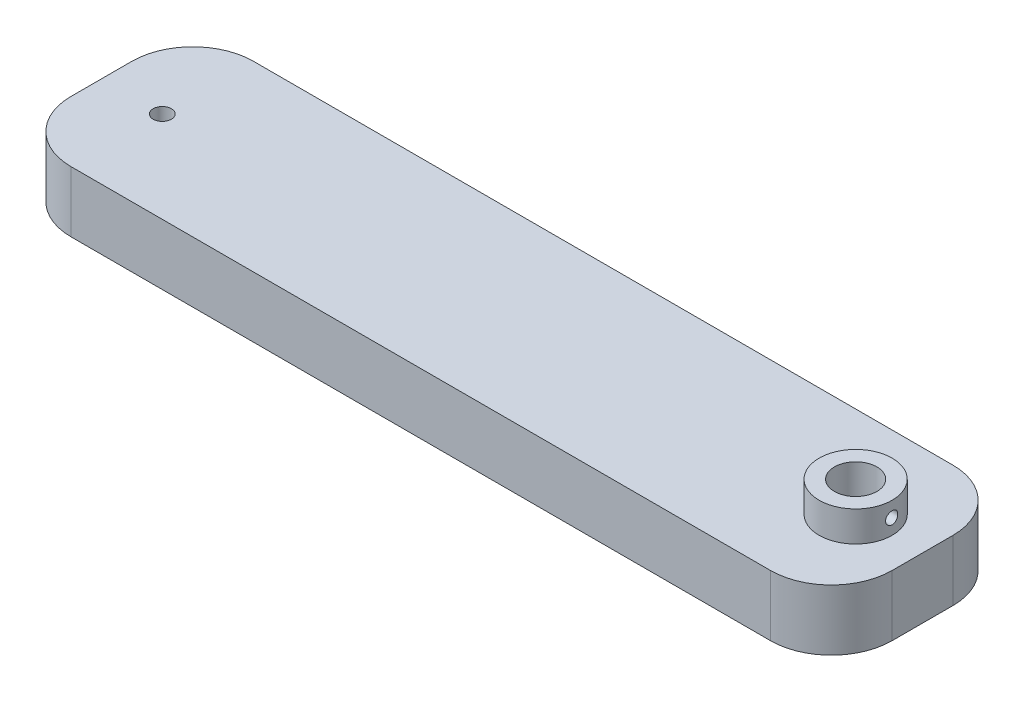
SolidWorks part; units mm, degrees
ref_plane "Alzado" through (0, 0, 0) normal (0, 0, 1) x (1, 0, 0)
ref_plane "Planta" through (0, 0, 0) normal (0, 1, 0) x (1, 0, 0)
ref_plane "Vista lateral" through (0, 0, 0) normal (1, 0, 0) x (0, 0, -1)
sketch "Croquis1" plane through (0, 0, 0) normal (0, 1, 0) x (1, 0, 0)
  line L1 (67.5, -15) -> (-67.5, -15)
  line L2 (67.5, -15) -> (67.5, 15)
  line L3 (67.5, 15) -> (-67.5, 15)
  line L4 (-67.5, -15) -> (-67.5, 15)
  line L5 (67.5, -15) -> (-67.5, 15) construction
  line L6 (67.5, 15) -> (-67.5, -15) construction
  point P0 (0, 0)
  point P12 (70, 0)
  dimension "D1" = 135
  dimension "D2" = 30
extrude "Saliente-Extruir1" add sketch "Croquis1" along normal blind 10
fillet "Redondeo3" radius 10 4 edges at (67.5, 5, 15) (-67.5, 5, 15) (-67.5, 5, -15) (67.5, 5, -15)
sketch "Croquis3" plane through (0, 10, 0) normal (0, 1, 0) x (1, 0, 0)
  line L2 (57.5, 15) -> (-57.5, 15) construction
  line L4 (-67.5, 5) -> (-67.5, -5) construction
  circle A0 centre (-57.5, 0) radius 1.5
  circle A1 centre (56.5, 0) radius 3.5
  dimension "D1" = 3
  dimension "D2" = 15
  dimension "D5" = 7
  dimension "D6" = 15
  dimension "D3" = 10
  dimension "D4" = 114
extrude "Cortar-Extruir2" cut sketch "Croquis3" against normal blind 10
sketch "Croquis4" plane through (0, 10, 0) normal (0, 1, 0) x (1, 0, 0)
  circle A0 centre (56.5, 0) radius 3.5
  circle A1 centre (56.5, 0) radius 6
  dimension "D1" = 7
  dimension "D2" = 12
extrude "Saliente-Extruir2" add sketch "Croquis4" along normal blind 5
ref_plane "Plano1" through (56.5, 0, 0) normal (1, 0, 0) x (0, 0, -1)
sketch "Croquis5" plane through (56.5, 0, 0) normal (1, 0, 0) x (0, 0, -1)
  line L0 (6, 15) -> (-6, 15) construction
  line L3 (6, 10) -> (6, 15) construction
  circle A0 centre (0, 12.5) radius 1
  dimension "D1" = 2
  dimension "D3" = 6
  dimension "D2" = 2.5
extrude "Cortar-Extruir3" cut sketch "Croquis5" along normal blind 6
